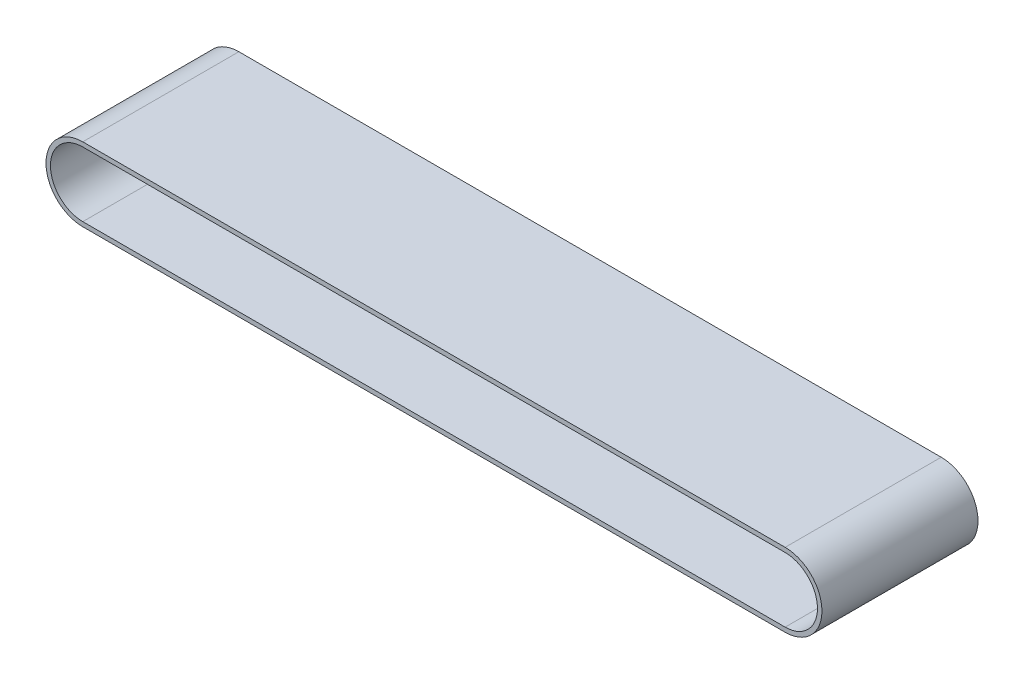
SolidWorks part; units mm, degrees
material "BUTYL"
ref_plane "Alzado" through (0, 0, 0) normal (0, 0, 1) x (1, 0, 0)
ref_plane "Planta" through (0, 0, 0) normal (0, 1, 0) x (1, 0, 0)
ref_plane "Vista lateral" through (0, 0, 0) normal (1, 0, 0) x (0, 0, -1)
sketch "Croquis2" plane through (0, 0, 0) normal (0, 0, 1) x (1, 0, 0)
  line L0 (0, 0) -> (1, 0) construction
  line L1 (0, 0) -> (0, 1) construction
  line L4 (-315, 18.5) -> (0, 18.5)
  line L5 (0, -10.5) -> (-315, -10.5)
  arc A1 (-315, -10.5) -> (-315, 18.5) centre (-315, 4) cw
  arc A2 (0, 18.5) -> (0, -10.5) centre (0, 4) cw
extrude "Extruir-Lámina1" add sketch "Croquis2" along normal mid plane 70 thin thin type one direction wall 2
